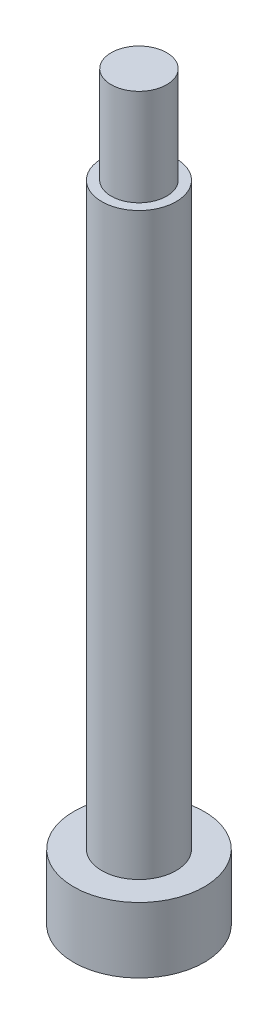
SolidWorks part; units mm, degrees
ref_plane "Front Plane" through (0, 0, 0) normal (0, 0, 1) x (1, 0, 0)
ref_plane "Top Plane" through (0, 0, 0) normal (0, 1, 0) x (1, 0, 0)
ref_plane "Right Plane" through (0, 0, 0) normal (1, 0, 0) x (0, 0, -1)
sketch "Sketch1" plane through (0, 0, 0) normal (0, 1, 0) x (1, 0, 0)
  circle A0 centre (0, 0) radius 3.4354
  dimension "D1" = 6.8707
extrude "Boss-Extrude1" add sketch "Sketch1" along normal blind 3.4417
sketch "Sketch2" plane through (0, 3.4417, 0) normal (0, 1, 0) x (1, 0, 0)
  circle A0 centre (0, 0) radius 1.9558
  dimension "D1" = 3.9116
extrude "Boss-Extrude2" add sketch "Sketch2" along normal blind 30.48
sketch "Sketch3" plane through (0, 33.9217, 0) normal (0, 1, 0) x (1, 0, 0)
  circle A0 centre (0, 0) radius 1.4605
  dimension "D1" = 2.921
extrude "Boss-Extrude3" add sketch "Sketch3" along normal blind 5.08
